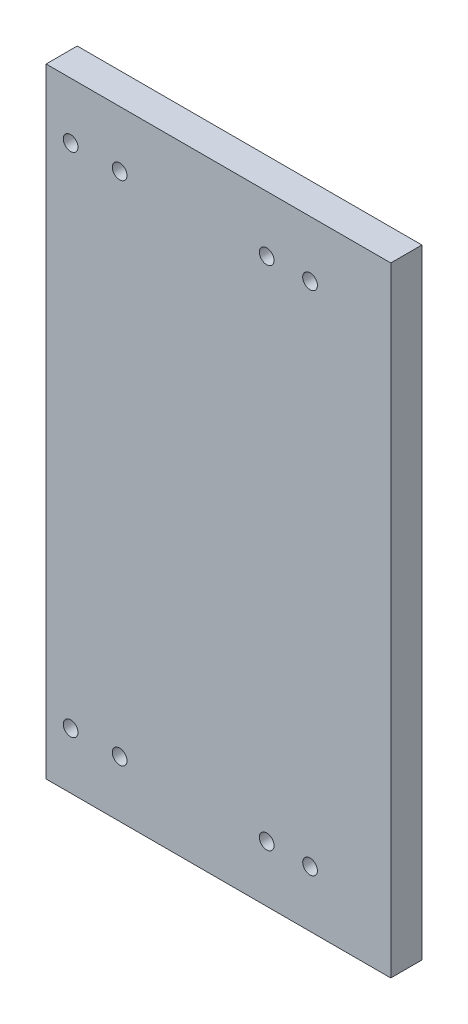
SolidWorks part; units mm, degrees
ref_plane "Front Plane" through (0, 0, 0) normal (0, 0, 1) x (1, 0, 0)
ref_plane "Top Plane" through (0, 0, 0) normal (0, 1, 0) x (1, 0, 0)
ref_plane "Right Plane" through (0, 0, 0) normal (1, 0, 0) x (0, 0, -1)
sketch "Sketch2" plane through (0, 0, 0) normal (0, 0, 1) x (1, 0, 0)
  line L1 (-5.1785, 27.0167) -> (-5.1785, 43.4867)
  line L3 (-5.1785, 90.1867) -> (72.1263, 90.1867) construction
  line L5 (-5.1785, 153.3567) -> (-5.1785, 136.8867)
  line L11 (-5.1785, 136.8867) -> (-5.1785, 43.4867)
  line L15 (65.1372, 153.3567) -> (65.1372, 27.0167)
  line L16 (65.1372, 153.3567) -> (-5.1785, 153.3567)
  line L17 (65.1372, 27.0167) -> (-5.1785, 27.0167)
  circle A0 centre (39.8215, 38.4867) radius 1.5
  circle A2 centre (9.8215, 38.4867) radius 1.5
  circle A3 centre (-0.1785, 38.4867) radius 1.5
  circle A4 centre (48.6715, 38.4867) radius 1.5
  circle A7 centre (48.6715, 141.8867) radius 1.5
  circle A8 centre (-0.1785, 141.8867) radius 1.5
  circle A9 centre (9.8215, 141.8867) radius 1.5
  circle A11 centre (39.8215, 141.8867) radius 1.5
  point P2 (0, 0)
  point P5 (0, 0)
  point P6 (0, 0)
  dimension "D5" = 3
  dimension "D6" = 3
  dimension "D8" = 3
  dimension "D4" = 30
  dimension "D7" = 5
  dimension "D9" = 10
extrude "Boss-Extrude3" add sketch "Sketch2" along normal blind 6.35
